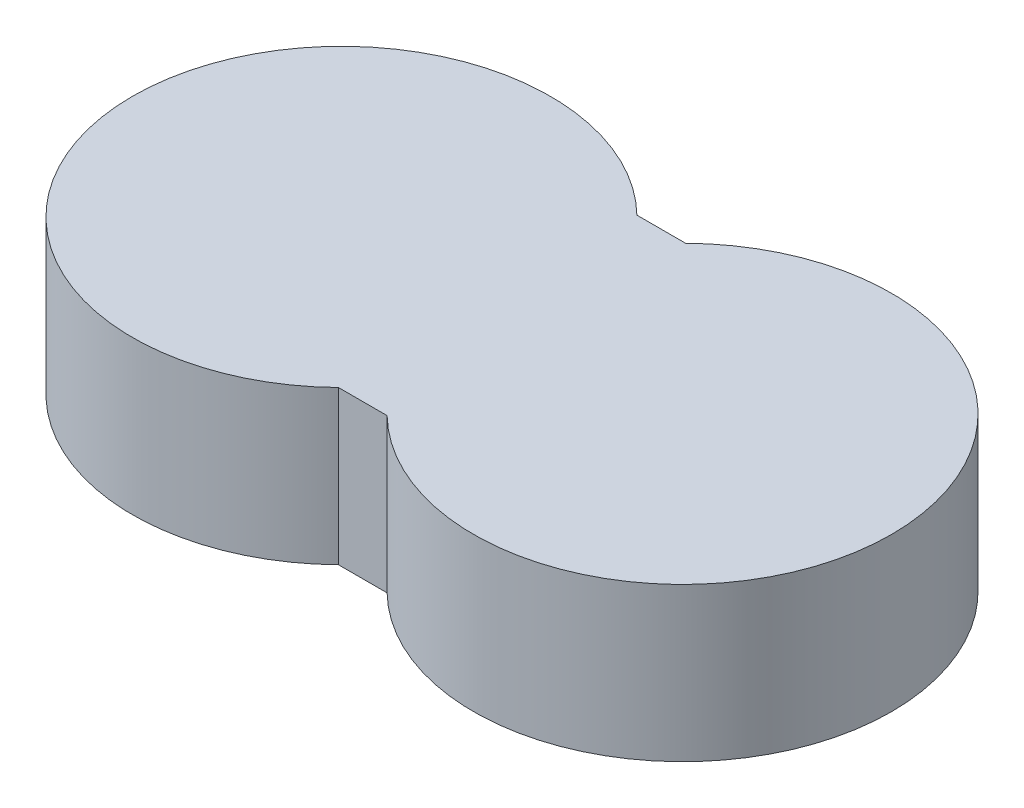
SolidWorks part; units mm, degrees
ref_plane "前视基准面" through (0, 0, 0) normal (0, 0, 1) x (1, 0, 0)
ref_plane "上视基准面" through (0, 0, 0) normal (0, 1, 0) x (1, 0, 0)
ref_plane "右视基准面" through (0, 0, 0) normal (1, 0, 0) x (0, 0, -1)
other "Configuration Table"
sketch "草图1" plane through (0, 0, 0) normal (0, 1, 0) x (1, 0, 0)
  line L0 (0, -1000) -> (0, -1.8) construction
  line L1 (0, 0) -> (4.0318, 0) construction
  line L2 (-0.2651, 1.8) -> (0.2651, 1.8)
  line L3 (0, 1.5) -> (0, 0) construction
  line L4 (-0.2651, -1.8) -> (0.2651, -1.8)
  line L5 (0, 1.8) -> (0, 1006.935) construction
  line L6 (0, 0) -> (0, 1.5) construction
  line L9 (-0.2854, -1.75) -> (0.2854, -1.75)
  line L10 (0, 0.05) -> (4.0318, 0.05)
  line L11 (-0.2854, 1.75) -> (0.2854, 1.75)
  arc A0 (0.2651, -1.8) -> (0.2651, 1.8) centre (2, 0) ccw
  arc A1 (-0.2651, 1.8) -> (-0.2651, -1.8) centre (-2, 0) ccw
  arc A4 (-0.2854, 1.75) -> (-0.2854, -1.75) centre (-2, 0) ccw
  arc A5 (0.2854, -1.75) -> (0.2854, 1.75) centre (2, 0) ccw
  dimension "D1" = 5
  dimension "D2" = 5
  dimension "D3" = 4
  dimension "D4" = 1.8
  dimension "D5" = 0.05
  dimension "D6" = 0.05
extrude "凸台-拉伸1" add sketch "草图1" along normal blind 1.8 contours L10 A5 L11 A4 | L9 A5 L10 A4
